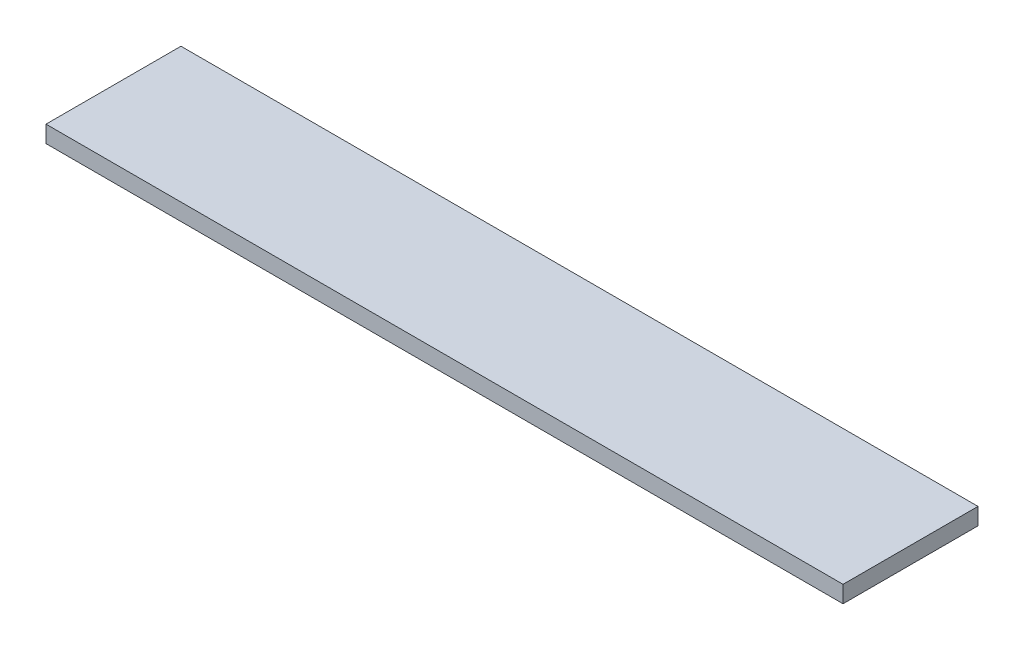
SolidWorks part; units mm, degrees
ref_plane "Front Plane" through (0, 0, 0) normal (0, 0, 1) x (1, 0, 0)
ref_plane "Top Plane" through (0, 0, 0) normal (0, 1, 0) x (1, 0, 0)
ref_plane "Right Plane" through (0, 0, 0) normal (1, 0, 0) x (0, 0, -1)
sketch "Sketch1" plane through (0, 0, 0) normal (1, 0, 0) x (0, 0, -1)
  line L1 (0, 0) -> (101.6, 0)
  line L2 (0, 0) -> (0, 12.7)
  line L3 (0, 12.7) -> (101.6, 12.7)
  line L4 (101.6, 0) -> (101.6, 12.7)
  dimension "D1" = 101.6
  dimension "D2" = 12.7
extrude "Boss-Extrude1" add sketch "Sketch1" along normal blind 600
ref_plane "Plane1" through (0, 0, -50.8) normal (0, 0, 1) x (1, 0, 0)
ref_plane "Plane2" through (300, 0, 0) normal (-1, 0, 0) x (0, 0, 1)
